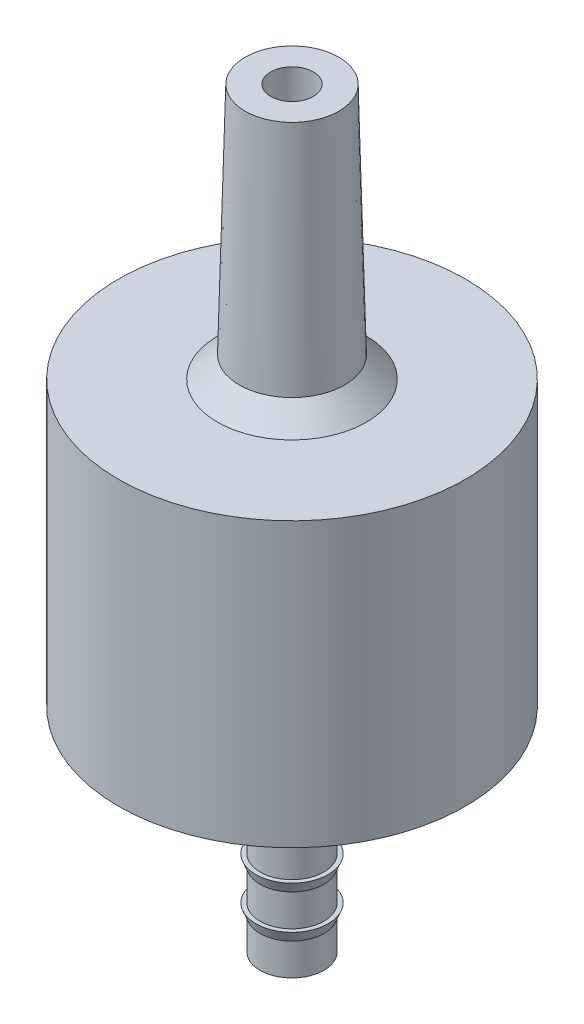
SolidWorks part; units mm, degrees
ref_plane "Plano frontal" through (0, 0, 0) normal (0, 0, 1) x (1, 0, 0)
ref_plane "Plano superior" through (0, 0, 0) normal (0, 1, 0) x (1, 0, 0)
ref_plane "Plano direito" through (0, 0, 0) normal (1, 0, 0) x (0, 0, -1)
sketch "Esboço1" plane through (0, 0, 0) normal (0, 0, 1) x (1, 0, 0)
  line L0 (0, 23.0581) -> (0, 0) construction
  line L1 (2.5, 0) -> (8.15, 0)
  line L2 (1.5, -13.3) -> (8.15, -13.3)
  line L3 (8.15, 0) -> (8.15, -13.3)
  line L4 (1, -23.3) -> (1.5, -23.3)
  line L5 (1.5, -23.3) -> (1.5, -21.8)
  line L6 (1.5, -21.8) -> (1.7, -21.3)
  line L7 (1.5, -21.3) -> (1.7, -21.3)
  line L8 (1.5, -19.3) -> (1.7, -19.3)
  line L9 (1.7, -19.3) -> (1.5, -19.8)
  line L10 (1.5, -17.3) -> (1.7, -17.3)
  line L11 (1.7, -17.3) -> (1.5, -17.8)
  line L12 (1.5, -15.3) -> (1.7, -15.3)
  line L13 (1.7, -15.3) -> (1.5, -15.8)
  line L14 (1.5, -15.3) -> (1.5, -13.3)
  line L15 (1.5, -17.3) -> (1.5, -15.8)
  line L16 (1.5, -19.3) -> (1.5, -17.8)
  line L17 (1.5, -21.3) -> (1.5, -19.8)
  line L19 (1, -23.3) -> (1.25, 0)
  line L20 (0, -23.3) -> (0, -18.0198) construction
  line L21 (0, 0) -> (1.25, 0) construction
  line L22 (0, 0) -> (0, -23.3) construction
  line L23 (0, 12) -> (1, 12) construction
  line L24 (1, 12) -> (1.25, 0)
  line L25 (1, 12) -> (2.2, 12)
  line L26 (2.2, 12) -> (2.5, 0)
  dimension "D1" = 8.15
  dimension "D2" = 13.3
  dimension "D3" = 1.5
  dimension "D4" = 10
  dimension "D5" = 1.5
  dimension "D6" = 0.2
  dimension "D7" = 0.5
  dimension "D8" = 1.5
  dimension "D9" = 1.5
  dimension "D10" = 1.5
  dimension "D11" = 1
  dimension "D12" = 1.25
  dimension "D13" = 1
  dimension "D14" = 12
  dimension "D15" = 2.2
  dimension "D16" = 2.5
revolve "Revolução1" add sketch "Esboço1" angle 360 about L0
sketch "Esboço2" plane through (0, 0, 0) normal (0, 0, 1) x (1, 0, 0)
  line L0 (1.5, -14.8) -> (2.5, -13.3)
  line L1 (-8.15, -13.3) -> (8.15, -13.3) construction
  line L2 (1.5, -15.3) -> (1.5, -13.3) construction
  line L3 (1.5, -14.8) -> (1.5, -13.3)
  line L4 (1.5, -13.3) -> (2.5, -13.3)
  line L5 (0, 0.658) -> (0, -16.2351) construction
  line L6 (2.5, 0) -> (2.475, 0.9997)
  line L7 (2.475, 0.9997) -> (3.5, 0)
  line L8 (2.5, 0) -> (3.5, 0)
  line L9 (8.15, 0) -> (-8.15, 0) construction
  line L10 (2.5, 0) -> (2.2, 12) construction
  dimension "D1" = 1.5
  dimension "D2" = 1
  dimension "D3" = 1
  dimension "D4" = 1
revolve "Revolução2" add sketch "Esboço2" angle 360 about L5
